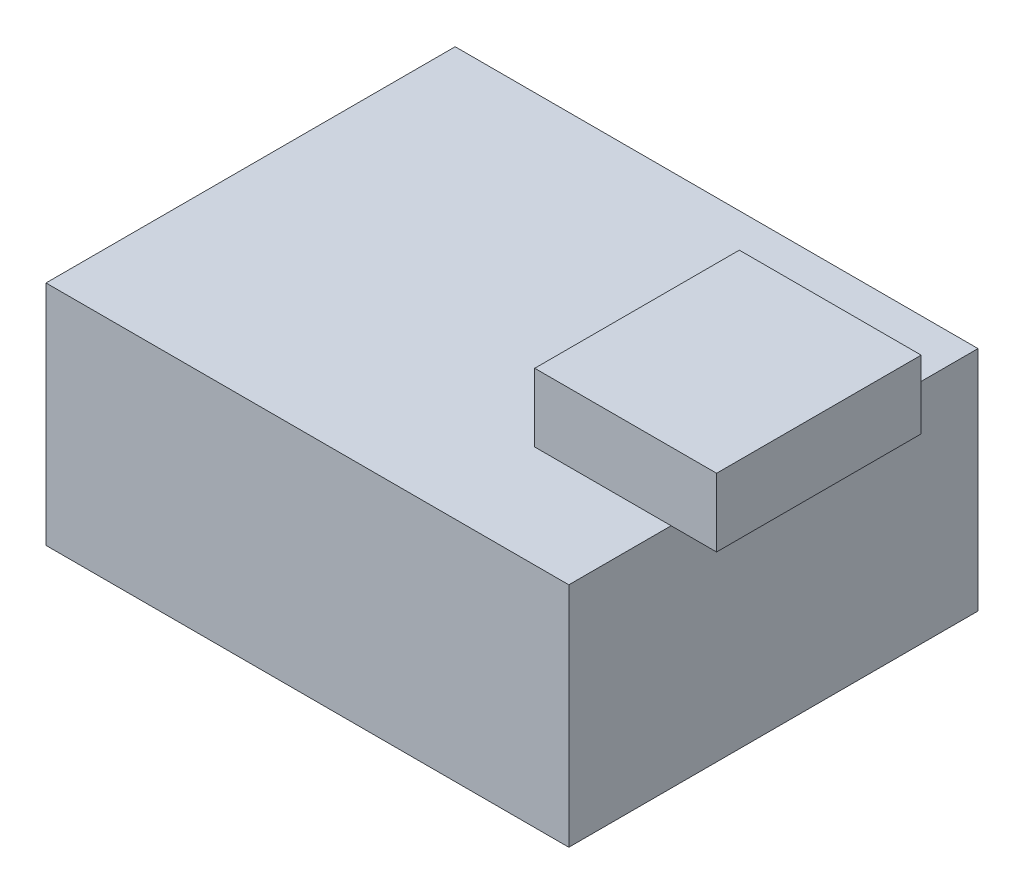
SolidWorks part; units mm, degrees
ref_plane "前视基准面" through (0, 0, 0) normal (0, 0, 1) x (1, 0, 0)
ref_plane "上视基准面" through (0, 0, 0) normal (0, 1, 0) x (1, 0, 0)
ref_plane "右视基准面" through (0, 0, 0) normal (1, 0, 0) x (0, 0, -1)
other "Configuration Table"
sketch "草图1" plane through (0, 0, 0) normal (0, 1, 0) x (1, 0, 0)
  line L1 (0, 0) -> (23, 0)
  line L2 (0, 0) -> (0, 18)
  line L3 (0, 18) -> (23, 18)
  line L4 (23, 0) -> (23, 18)
  dimension "D1" = 23
  dimension "D2" = 18
extrude "凸台-拉伸1" add sketch "草图1" along normal blind 10
sketch "草图2" plane through (0, 10, 0) normal (0, 1, 0) x (1, 0, 0)
  line L0 (23, 0) -> (23, 18) construction
  line L1 (17, 13.5) -> (25, 13.5)
  line L2 (17, 13.5) -> (17, 4.5)
  line L3 (17, 4.5) -> (25, 4.5)
  line L4 (25, 13.5) -> (25, 4.5)
  point P6 (23, 9)
  point P7 (17, 9)
  dimension "D1" = 9
  dimension "D2" = 8
  dimension "D3" = 2
extrude "凸台-拉伸2" add sketch "草图2" along normal blind 3
